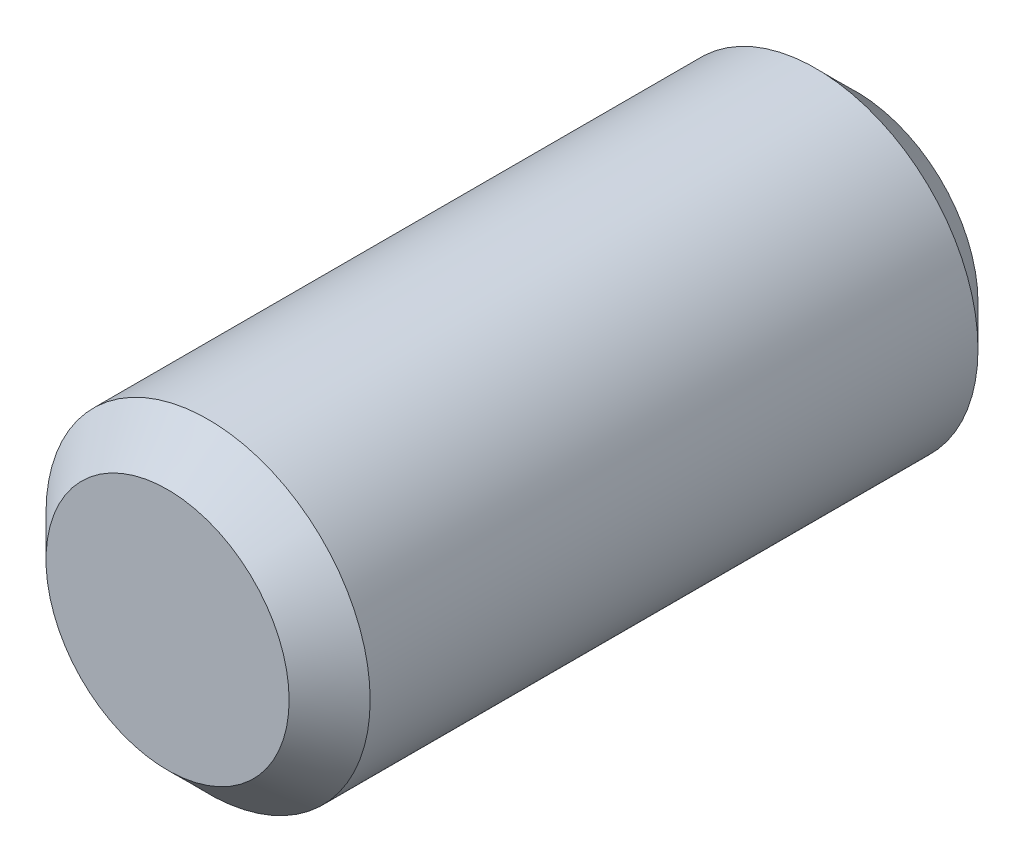
SolidWorks part; units mm, degrees
ref_plane "前视基准面" through (0, 0, 0) normal (0, 0, 1) x (1, 0, 0)
ref_plane "上视基准面" through (0, 0, 0) normal (0, 1, 0) x (1, 0, 0)
ref_plane "右视基准面" through (0, 0, 0) normal (1, 0, 0) x (0, 0, -1)
sketch "草图1" plane through (0, 0, 0) normal (0, 0, 1) x (1, 0, 0)
  circle A0 centre (0, 0) radius 2
  dimension "D1" = 4
extrude "拉伸1" add sketch "草图1" along normal blind 8.5
chamfer "倒角1" distance 0.5 angle 45 2 edges at (2, 0, 0) (2, 0, 8.5)
